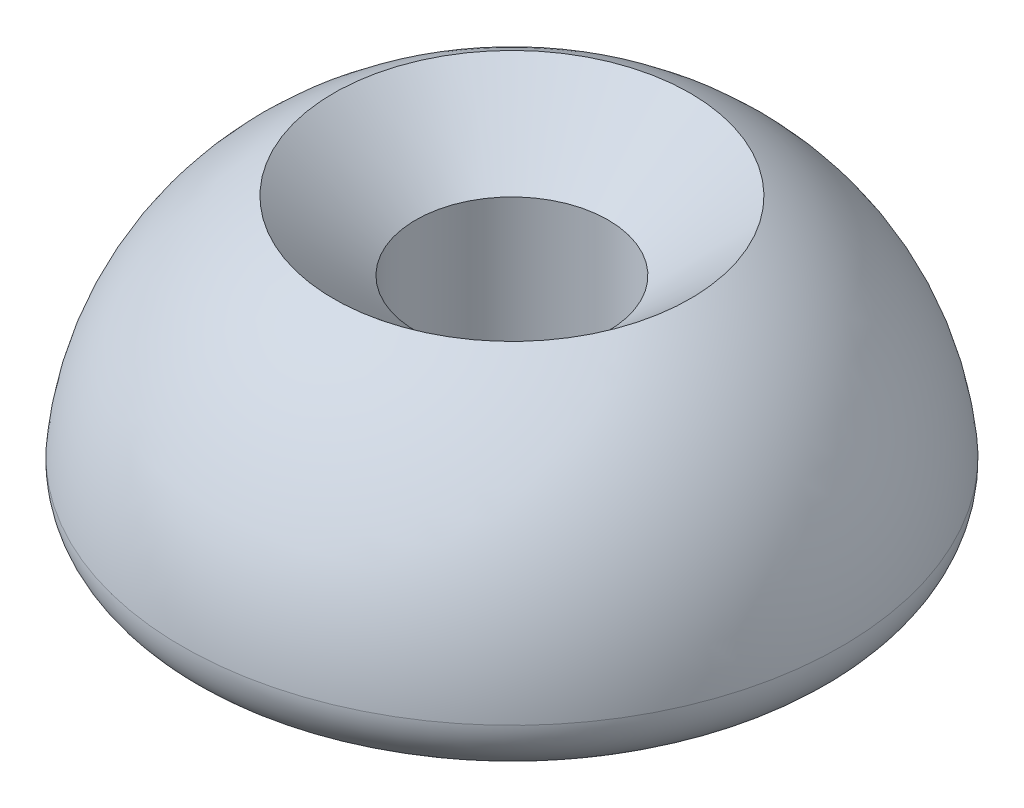
SolidWorks part; units mm, degrees
ref_plane "Plan de face" through (0, 0, 0) normal (0, 0, 1) x (1, 0, 0)
ref_plane "Plan de dessus" through (0, 0, 0) normal (0, 1, 0) x (1, 0, 0)
ref_plane "Plan de droite" through (0, 0, 0) normal (1, 0, 0) x (0, 0, -1)
sketch "Esquisse1" plane through (0, 0, 0) normal (0, 0, 1) x (1, 0, 0)
  line L0 (0, -84.7912) -> (0, 78.2228) construction
  line L1 (0, -64.8708) -> (50, -64.8708)
  line L2 (0, -64.8708) -> (0, -54.7162)
  line L3 (0, -54.7162) -> (58.25, -54.7162)
  line L4 (0, -54.7162) -> (0, -14.8708)
  line L5 (0, -14.8708) -> (31.5, -14.8708)
  line L6 (17, -64.8708) -> (17, -27.0377)
  line L7 (17, -27.0377) -> (0, -27.0377)
  line L8 (17, -27.0377) -> (31.5, -14.8708)
  arc A1 (58.25, -54.7162) -> (31.5, -14.8708) centre (8.4554, -59.2436) ccw
  arc A2 (46.5095, -64.8708) -> (58.25, -54.7162) centre (48.2547, -55.0242) ccw
  dimension "D3" = 20
  dimension "D6" = 100
  dimension "D5" = 50
  dimension "D1" = 84.7912
  dimension "D2" = 50
  dimension "D4" = 58.25
  dimension "D7" = 31.5
  dimension "D8" = 64.8708
  dimension "D9" = 9.8465
  dimension "D10" = 17
  dimension "D11" = 40
revolve "Révolution1" add sketch "Esquisse1" angle 360 about L0
